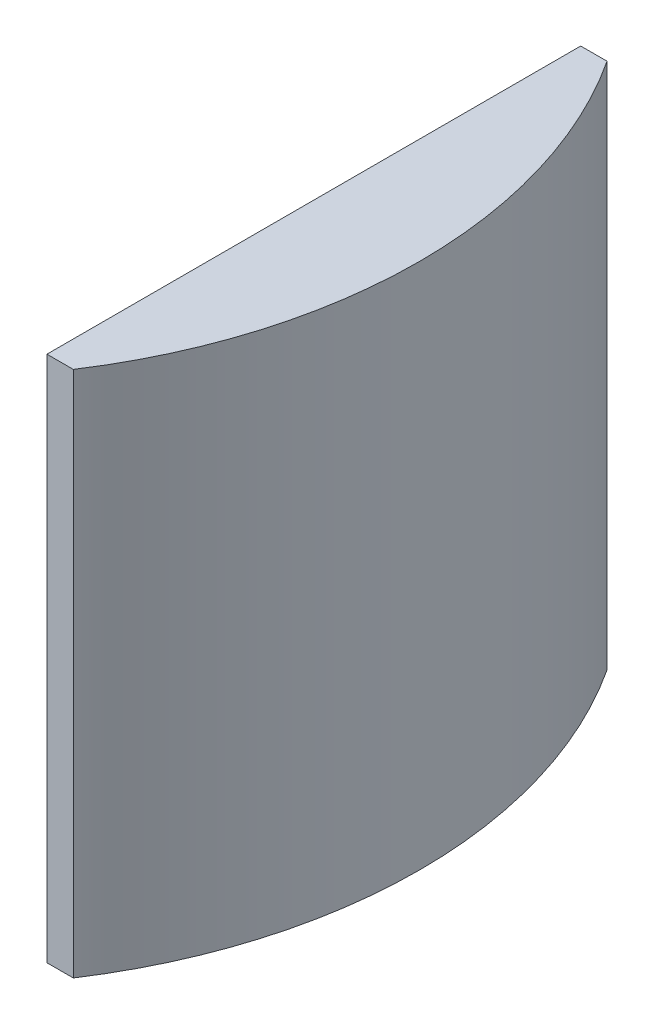
SolidWorks part; units mm, degrees
ref_plane "前视基准面" through (0, 0, 0) normal (0, 0, 1) x (1, 0, 0)
ref_plane "上视基准面" through (0, 0, 0) normal (0, 1, 0) x (1, 0, 0)
ref_plane "右视基准面" through (0, 0, 0) normal (1, 0, 0) x (0, 0, -1)
sketch "草图1" plane through (0, 0, 0) normal (0, 1, 0) x (1, 0, 0)
  line L1 (-32.3947, 13.7379) -> (-1.4757, 13.7379)
  line L2 (-32.3947, 13.7379) -> (-32.3947, -13.7379)
  line L3 (-32.3947, -13.7379) -> (-1.4757, -13.7379)
  line L4 (-1.4757, 13.7379) -> (-1.4757, -13.7379)
  line L5 (-32.3947, 13.7379) -> (-1.4757, -13.7379) construction
  line L6 (-32.3947, -13.7379) -> (-1.4757, 13.7379) construction
  circle A0 centre (-16.9352, 0) radius 18.4811
  point P6 (-1.4757, 9.873)
  point P7 (-1.4757, -10.127)
  dimension "D1" = 20
extrude "凸台-拉伸1" add sketch "草图1" along normal blind 20 contours L4 A0
sketch "草图2" plane through (-1.4757, 0, 0) normal (-1, 0, 0) x (0, 0, 1)
  line L0 (-10.127, 0) -> (10.127, 0) construction
  line L1 (-10.127, 20) -> (10.127, 20)
  line L2 (-10.127, 20) -> (-10.127, 0)
  line L3 (-10.127, 0) -> (10.127, 0)
  line L4 (10.127, 20) -> (10.127, 0)
  line L5 (10.127, 20) -> (10.127, 0) construction
extrude "凸台-拉伸2" add sketch "草图2" along normal blind 1
sketch "草图3" plane through (-2.4757, 0, 0) normal (-1, 0, 0) x (0, 0, 1)
  line L0 (-10.127, 20) -> (10.127, 0)
  point P4 (0, 10)
